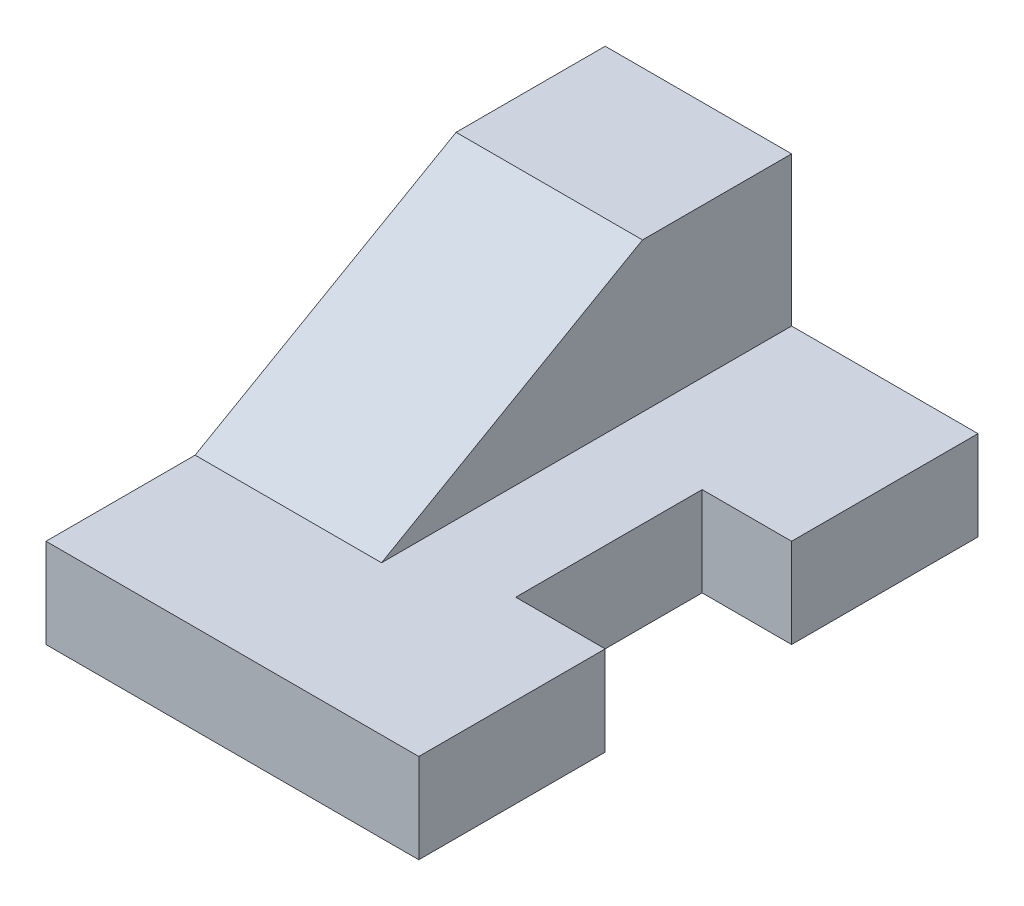
SolidWorks part; units mm, degrees
ref_plane "Front Plane" through (0, 0, 0) normal (0, 0, 1) x (1, 0, 0)
ref_plane "Top Plane" through (0, 0, 0) normal (0, 1, 0) x (1, 0, 0)
ref_plane "Right Plane" through (0, 0, 0) normal (1, 0, 0) x (0, 0, -1)
sketch "Sketch1" plane through (0, 0, 0) normal (0, 1, 0) x (1, 0, 0)
  line L0 (0, 0) -> (0, 75)
  line L1 (0, 75) -> (50, 75)
  line L2 (50, 75) -> (50, 50)
  line L3 (50, 50) -> (38, 50)
  line L4 (38, 50) -> (38, 25)
  line L5 (38, 25) -> (50, 25)
  line L6 (50, 25) -> (50, 0)
  line L7 (50, 0) -> (0, 0)
  dimension "D1" = 50
  dimension "D2" = 25
  dimension "D3" = 25
  dimension "D4" = 25
  dimension "D5" = 12
  dimension "D6" = 12
extrude "Boss-Extrude1" add sketch "Sketch1" along normal blind 12
sketch "Sketch6" plane through (0, 0, 0) normal (-1, 0, 0) x (0, 0, 1)
  line L0 (-55, 32) -> (-20, 12)
  line L1 (-75, 12) -> (-55, 12)
  line L2 (-75, 12) -> (-75, 32)
  line L3 (-75, 32) -> (-55, 32)
  line L5 (-75, 12) -> (0, 12) construction
  line L6 (-20, 12) -> (-55, 12)
  dimension "D1" = 20
  dimension "D2" = 20
  dimension "D3" = 20
extrude "Boss-Extrude3" add sketch "Sketch6" against normal blind 25
